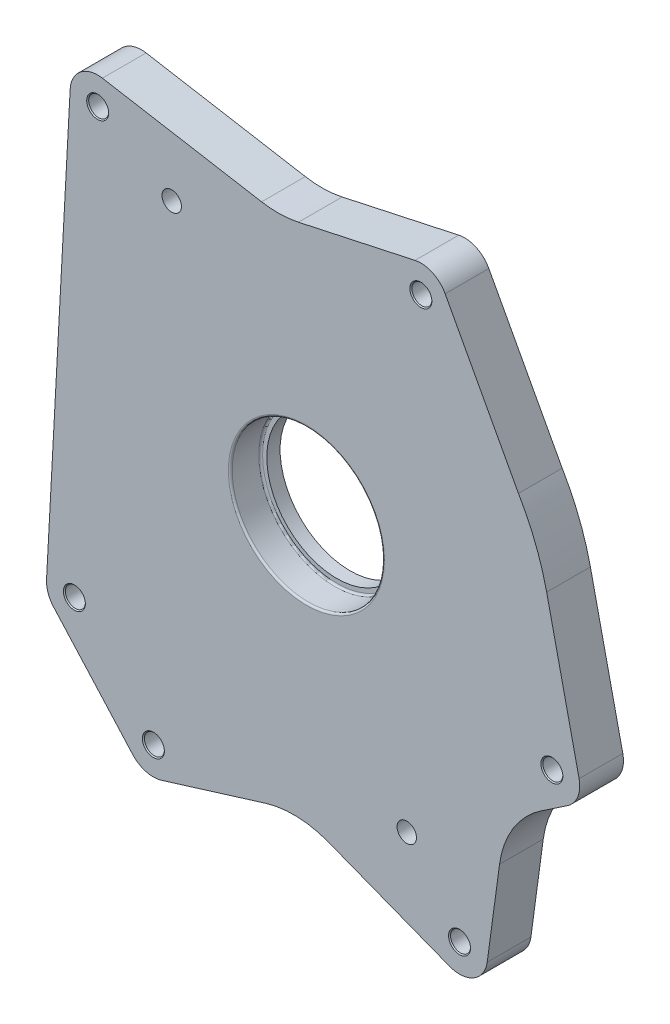
SolidWorks part; units mm, degrees
material "6061-T6 (SS)"
ref_plane "Front Plane" through (0, 0, 0) normal (0, 0, 1) x (1, 0, 0)
ref_plane "Top Plane" through (0, 0, 0) normal (0, 1, 0) x (1, 0, 0)
ref_plane "Right Plane" through (0, 0, 0) normal (1, 0, 0) x (0, 0, -1)
sketch "Sketch1" plane through (0, 0, 0) normal (0, 0, 1) x (1, 0, 0)
  line L0 (75.2603, -167.8065) -> (-4.7006, -136.7784)
  line L1 (-76.1562, -158.8451) -> (-4.7006, -136.7784)
  line L2 (-91.4027, -154.6255) -> (-132.9618, -108.3053)
  line L3 (137.307, -63.6581) -> (104.6792, -85.5609)
  line L4 (95.1022, -156.1046) -> (104.6792, -85.5609)
  line L5 (143.448, -48.2848) -> (126.3947, 28.1467)
  line L6 (72.99, 137.3728) -> (111.5613, 65.705)
  line L9 (57.1543, 144.6728) -> (-13.8203, 129.3107)
  line L13 (-107.31, 145.452) -> (-13.8203, 129.3107)
  line L14 (-124.2557, 131.9473) -> (-136.6908, -97.7162)
  arc A2 (-107.31, 145.452) -> (-124.2557, 131.9473) centre (-109.777, 131.1634) ccw
  circle A3 centre (-109.777, 131.1634) radius 1.5
  arc A6 (72.99, 137.3728) -> (57.1543, 144.6728) centre (60.2218, 130.501) ccw
  circle A7 centre (-70.8267, 107.741) radius 5.1006
  arc A9 (-136.6908, -97.7162) -> (-132.9618, -108.3053) centre (-122.0435, -98.5093) ccw
  circle A10 centre (-122.0435, -98.5093) radius 1.5
  arc A12 (-91.4027, -154.6255) -> (-76.1562, -158.8451) centre (-80.4845, -144.8295) ccw
  circle A13 centre (-80.4845, -144.8295) radius 1.5
  arc A15 (75.2603, -167.8065) -> (95.1022, -156.1046) centre (80.5668, -154.1313) ccw
  arc A17 (137.307, -63.6581) -> (143.448, -48.2848) centre (129.1313, -51.4791) ccw
  circle A18 centre (52.8018, -118.0094) radius 5.1006
  circle A23 centre (80.5668, -154.1313) radius 1.5
  circle A26 centre (60.2218, 130.501) radius 5.5 construction
  circle A27 centre (129.1313, -51.4791) radius 1.5
  arc A30 (126.3947, 28.1467) -> (111.5613, 65.705) centre (-0.017, -0.0702) ccw
  circle A31 centre (60.2218, 130.501) radius 1.5
  circle A32 centre (129.1313, -51.4791) radius 5.5 construction
  circle A33 centre (-70.8267, 107.741) radius 5 construction
  circle A34 centre (52.8018, -118.0094) radius 5 construction
  dimension "D1" = 14.5
  dimension "D2" = 3
  dimension "D3" = 10.2012
extrude "Boss-Extrude1" add sketch "Sketch1" along normal blind 23
fillet "Fillet2" radius 50.8 3 edges at (-13.8203, 129.3107, 11.5) (104.6792, -85.5609, 11.5) (-4.7006, -136.7784, 11.5)
sketch "Sketch2" plane through (0, 0, 23) normal (0, 0, -1) x (-1, 0, 0)
  circle A0 centre (0, 0) radius 40.05
  dimension "D1" = 80.1
extrude "Cut-Extrude1" cut sketch "Sketch2" along normal blind 16
sketch "Sketch5" plane through (0, 0, 23) normal (0, 0, -1) x (-1, 0, 0)
  circle A0 centre (0, 0) radius 36.83
  dimension "D1" = 73.66
extrude "Cut-Extrude2" cut sketch "Sketch5" along normal blind 25.4
sketch "Sketch6" plane through (0, 0, 0) normal (0, 0, 1) x (1, 0, 0)
  circle A0 centre (0, 0) radius 50.8 construction
  point P14 (0, 0)
  dimension "D2" = 101.6
fillet "Fillet5" radius 1 1 edges at (-40.05, 0, 23)
fillet "Fillet6" radius 1 1 edges at (-40.05, 0, 7)
hole_wizard "M10 Clearance Hole4" positions "Sketch15" profile "Sketch16" hole size "M10" standard "ANSI Metric" end condition through all
sketch "Sketch15" plane through (0, 0, 23) normal (0, 0, 1) x (1, 0, 0)
  point P0 (60.2218, 130.501)
  point P3 (-109.777, 131.1634)
  point P6 (129.1313, -51.4791)
  point P9 (80.5668, -154.1313)
  point P12 (-80.4845, -144.8295)
  point P15 (-122.0435, -98.5093)
sketch "Sketch16" plane through (60.2218, 130.501, 23) normal (1, 0, 0) x (0, -1, 0)
  line L0 (0, 0) -> (0, 23)
  line L1 (0, 23) -> (5.25, 23)
  line L2 (5.25, 23) -> (5.25, 0.525)
  line L3 (5.25, 0.525) -> (5.775, 0)
  line L5 (5.775, 0) -> (0, 0)
  line L6 (-5.25, 0.525) -> (-5.775, 0) construction
  line L11 (0, -6.35) -> (0, 107.95) construction
  dimension "Thru Hole Dia." = 10.5
  dimension "Thru Hole Depth" = 23
  dimension "Near C'Sink Dia." = 11.55
  dimension "Near C'Sink Angle" = 90
